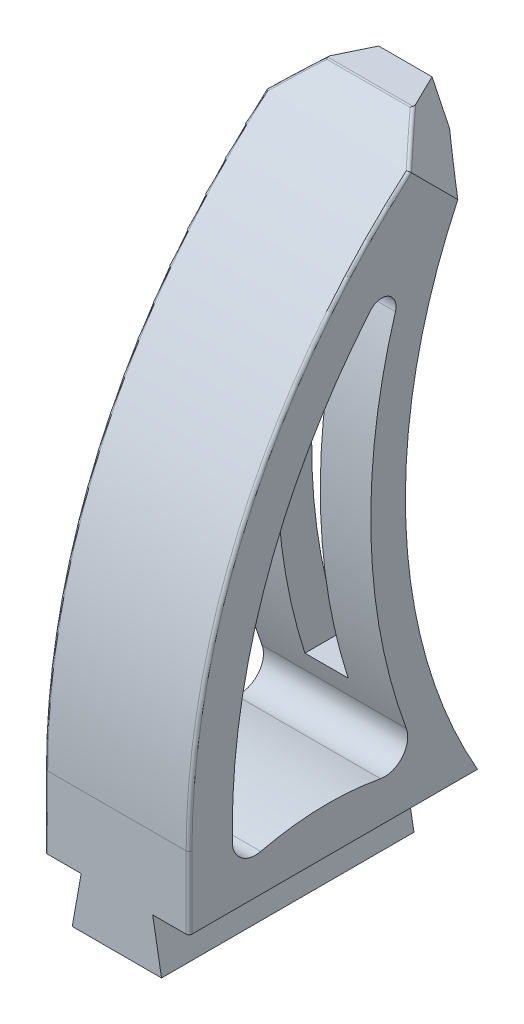
SolidWorks part; units mm, degrees
material "ABS"
ref_plane "Front Plane" through (0, 0, 0) normal (0, 0, 1) x (1, 0, 0)
ref_plane "Top Plane" through (0, 0, 0) normal (0, 1, 0) x (1, 0, 0)
ref_plane "Right Plane" through (0, 0, 0) normal (1, 0, 0) x (0, 0, -1)
sketch "Sketch1" plane through (0, 0, 0) normal (0, 0, 1) x (1, 0, 0)
  line L0 (-3.9688, 0) -> (3.9688, 0)
  line L1 (0, 0) -> (0, 4.5016) construction
  line L2 (-3.175, 4.5016) -> (3.175, 4.5016) construction
  line L3 (3.175, 4.5016) -> (3.9688, 0)
  line L4 (-3.175, 4.5016) -> (-3.9688, 0)
  line L5 (3.175, 4.5016) -> (6.35, 4.5016)
  line L6 (-3.175, 4.5016) -> (-6.35, 4.5016)
  line L7 (-6.35, 4.5016) -> (-6.35, 55.3016)
  line L8 (-6.35, 55.3016) -> (6.35, 55.3016)
  line L9 (6.35, 55.3016) -> (6.35, 4.5016)
  dimension "D1" = 7.9375
  dimension "D2" = 6.35
  dimension "D3" = 12.7
  dimension "D4" = 50.8
  dimension "D5" = 20
extrude "Boss-Extrude1" add sketch "Sketch1" along normal mid plane 25.4
sketch "Sketch2" plane through (6.35, 0, 0) normal (1, 0, 0) x (0, 0, -1)
  line L0 (12.7, 55.3016) -> (9.525, 55.3016) construction
  line L1 (-12.7, 55.3016) -> (12.7, 55.3016) construction
  line L2 (9.525, 55.3016) -> (-12.7, 55.3016)
  line L3 (-12.7, 55.3016) -> (-12.7, 10.8516)
  line L4 (-12.7, 4.5016) -> (-12.7, 55.3016) construction
  line L5 (-12.7, 10.8516) -> (-12.7, 4.5016) construction
  arc A0 (9.525, 55.3016) -> (-12.7, 10.8516) centre (42.8625, 10.8516) ccw
  dimension "D1" = 6.35
  dimension "D2" = 3.175
sketch "Sketch3" plane through (6.35, 0, 0) normal (1, 0, 0) x (0, 0, -1)
  line L0 (-12.7, 0) -> (12.7, 0) construction
  line L1 (12.7, 4.5016) -> (9.525, 4.5016)
  line L2 (12.7, 4.5016) -> (12.7, 0)
  line L3 (12.7, 0) -> (9.525, 0)
  line L4 (9.525, 4.5016) -> (9.525, 0)
  dimension "D1" = 3.175
sketch "Sketch4" plane through (6.35, 0, 0) normal (1, 0, 0) x (0, 0, -1)
  line L0 (12.7, 55.3016) -> (12.7, 52.1266) construction
  line L1 (12.7, 4.5016) -> (12.7, 55.3016) construction
  line L2 (6.35, 28.3141) -> (12.7, 28.3141) construction
  line L3 (12.7, 52.1266) -> (12.7, 4.5016)
  arc A0 (12.7, 4.5016) -> (12.7, 52.1266) centre (54.1734, 28.3141) cw
  dimension "D1" = 3.175
  dimension "D2" = 6.35
sketch "Sketch17" plane through (0, 0, 12.7) normal (0, 0, 1) x (1, 0, 0)
  line L3 (-3.9688, 0) -> (3.9688, 0)
  line L4 (-3.175, 4.5016) -> (-3.9688, 0)
  line L5 (-3.9688, 0) -> (3.9688, 0)
  line L6 (3.9688, 0) -> (3.175, 4.5016)
  line L7 (-3.175, 4.5016) -> (-3.9688, 0)
  line L8 (3.9688, 0) -> (3.175, 4.5016)
  line L14 (3.175, 4.5016) -> (6.35, 4.5016)
  line L15 (3.175, 4.5016) -> (6.35, 4.5016)
  line L16 (6.35, 4.5016) -> (6.35, 55.3016)
  line L17 (6.35, 4.5016) -> (6.35, 55.3016)
  line L18 (6.35, 55.3016) -> (-6.35, 55.3016)
  line L19 (6.35, 55.3016) -> (-6.35, 55.3016)
  line L20 (-6.35, 55.3016) -> (-6.35, 4.5016)
  line L21 (-6.35, 55.3016) -> (-6.35, 4.5016)
  line L22 (-6.35, 4.5016) -> (-3.175, 4.5016)
  line L23 (-6.35, 4.5016) -> (-3.175, 4.5016)
  dimension "D1" = 0
extrude "Kes-Ekstrüzyon1" cut sketch "Sketch2" against normal blind 22.86
extrude "Kes-Ekstrüzyon2" cut sketch "Sketch3" against normal blind 22.86 contours L2 L3 L4 L1
extrude "Kes-Ekstrüzyon3" cut sketch "Sketch4" against normal blind 22.86 contours A0 L3
sketch "Çizim1" plane through (0, 0, 0) normal (1, 0, 0) x (0, 0, -1)
  line L0 (-8.89, 10.8516) -> (-8.89, 7.0416)
  line L1 (-8.89, 7.0416) -> (7.9632, 7.0416) construction
  arc A0 (-8.89, 7.0416) -> (7.9632, 7.0416) centre (-0.4634, -16.9199) cw
  arc A4 (7.5646, 48.6984) -> (7.9632, 7.0416) centre (54.1734, 28.3141) ccw
  arc A7 (7.5646, 48.6984) -> (-8.89, 10.8516) centre (42.8625, 10.8516) ccw
  dimension "D4" = 25.4
extrude "Kes-Ekstrüzyon4" cut sketch "Çizim1" against normal mid plane 22.86
fillet "Radyus1" radius 2.032 2 edges at (0, 7.0416, 8.89) (0, 7.0416, -7.9632)
fillet "Radyus2" radius 1.27 1 edges at (0, 48.6984, -7.5646)
ref_plane "Düzlem1" through (0, 0, -2.54) normal (0, 0, 1) x (1, 0, 0)
sketch "Çizim2" plane through (0, 0, -2.54) normal (0, 0, 1) x (1, 0, 0)
  line L0 (0, 0) -> (0, 4.5016) construction
  line L2 (-1.905, 38.1) -> (1.905, 38.1)
  line L3 (-1.905, 38.1) -> (-1.905, 12.7)
  line L4 (-1.905, 12.7) -> (1.905, 12.7)
  line L5 (1.905, 38.1) -> (1.905, 12.7)
  line L6 (0, 4.5016) -> (0, 12.7) construction
  dimension "D1" = 12.7
  dimension "D2" = 3.81
  dimension "D3" = 25.4
extrude "Kes-Ekstrüzyon5" cut sketch "Çizim2" against normal blind 22.86 contours L2 L5 L4 L3
sketch "Çizim3" plane through (0, 0, -9.525) normal (0, 0, -1) x (-1, 0, 0)
  line L0 (3.9688, 0) -> (-3.9688, 0) construction
  line L1 (-4.2256, -0.0762) -> (4.2256, -0.0762)
  line L2 (-4.2256, -0.0762) -> (-4.2256, 0.0762)
  line L3 (-4.2256, 0.0762) -> (4.2256, 0.0762)
  line L4 (4.2256, -0.0762) -> (4.2256, 0.0762)
  line L5 (-4.2256, -0.0762) -> (4.2256, 0.0762) construction
  line L6 (-4.2256, 0.0762) -> (4.2256, -0.0762) construction
  point P0 (0, 0)
  dimension "D1" = 0.0762
extrude "Kes-Ekstrüzyon6" cut sketch "Çizim3" against normal blind 22.86
sketch "Çizim4" plane through (0, 0, -9.525) normal (0, 0, -1) x (-1, 0, 0)
  line L0 (-3.9688, 0) -> (-3.175, 4.5016) construction
  line L1 (3.175, 4.5016) -> (3.9688, 0) construction
  line L2 (3.1492, 4.5016) -> (3.9437, -0.0044)
  line L3 (-3.9437, -0.0044) -> (-3.15, 4.4972)
  line L4 (3.175, 4.5016) -> (3.9688, 0)
  line L5 (-3.9688, 0) -> (-3.175, 4.5016)
  line L6 (-3.15, 4.4972) -> (-3.1492, 4.5016)
  line L7 (3.175, 4.5016) -> (-3.175, 4.5016) construction
  line L8 (-3.1492, 4.5016) -> (-3.175, 4.5016)
  line L9 (3.15, 4.4972) -> (3.9437, -0.0044) construction
  line L10 (3.1492, 4.5016) -> (3.175, 4.5016)
  line L11 (3.9437, -0.0044) -> (3.9688, 0)
  line L12 (-3.9688, 0) -> (-3.9437, -0.0044)
  dimension "D1" = 0.0254
extrude "Kes-Ekstrüzyon7" cut sketch "Çizim4" against normal blind 22.86
ref_plane "Düzlem4" through (0, 23.876, 0) normal (0, 1, 0) x (1, 0, 0)
ref_plane "Düzlem6" through (0, 6.3881, 6.3881) normal (0, 0.7071, 0.7071) x (-1, 0, 0)
ref_plane "Düzlem7" through (0, 23.271, 23.271) normal (0, 0.7071, 0.7071) x (-1, 0, 0)
sketch "Çizim7" plane through (0, 23.271, 23.271) normal (0, 0.7071, 0.7071) x (-1, 0, 0)
  line L0 (2.3499, -48.0844) -> (8.543, -39.081)
  line L1 (-6.35, -48.0844) -> (6.35, -48.0844) construction
  line L2 (8.543, -39.081) -> (8.543, -48.0844)
  line L3 (8.543, -48.0844) -> (2.3499, -48.0844)
  line L4 (0, -48.0844) -> (0, -51.8876) construction
  line L5 (-8.543, -48.0844) -> (-2.3499, -48.0844)
  line L6 (-8.543, -39.081) -> (-8.543, -48.0844)
  line L7 (-2.3499, -48.0844) -> (-8.543, -39.081)
extrude "Kes-Ekstrüzyon8" cut sketch "Çizim7" against normal blind 22.86
fillet "Radyus3" radius 0.254 7 edges at (6.35, 7.6766, 12.7) (-6.35, 7.6766, 12.7) (5.1199, 54.2008, -8.1057) (6.35, 34.0806, 7.6113) (-6.35, 34.0806, 7.6113) (-5.1199, 54.2008, -8.1057) (0, 55.3016, -9.525)
